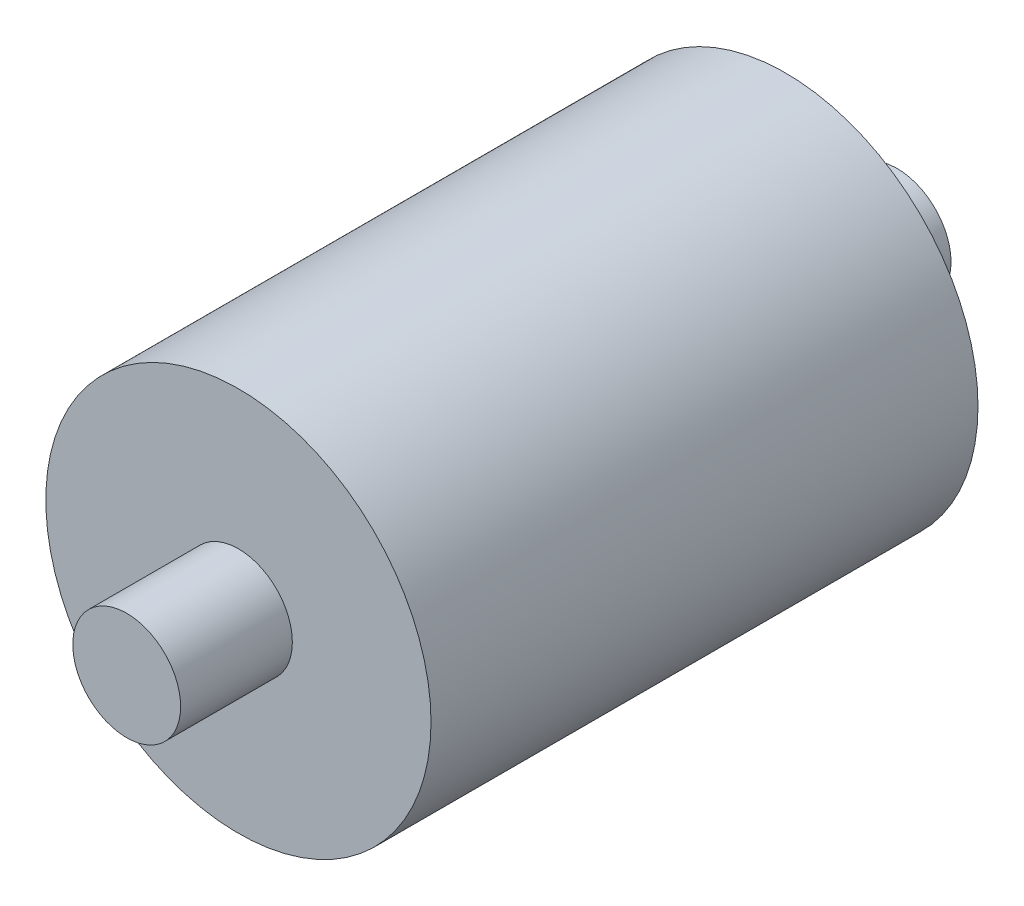
SolidWorks part; units mm, degrees
material "Acero inoxidable al cromo"
ref_plane "Alzado" through (0, 0, 0) normal (0, 0, 1) x (1, 0, 0)
ref_plane "Planta" through (0, 0, 0) normal (0, 1, 0) x (1, 0, 0)
ref_plane "Vista lateral" through (0, 0, 0) normal (1, 0, 0) x (0, 0, -1)
sketch "Croquis1" plane through (0, 0, 0) normal (0, 0, 1) x (1, 0, 0)
  circle A0 centre (0, 0) radius 25
  dimension "D1" = 50
extrude "Saliente-Extruir1" add sketch "Croquis1" along normal mid plane 71
sketch "Croquis2" plane through (0, 0, 0) normal (0, 0, 1) x (1, 0, 0)
  circle A0 centre (0, 0) radius 7
extrude "Saliente-Extruir2" add sketch "Croquis2" along normal mid plane 100
sketch "Croquis3" plane through (0, 0, 0) normal (0, 0, 1) x (1, 0, 0)
  circle A0 centre (0, 0) radius 30.02
